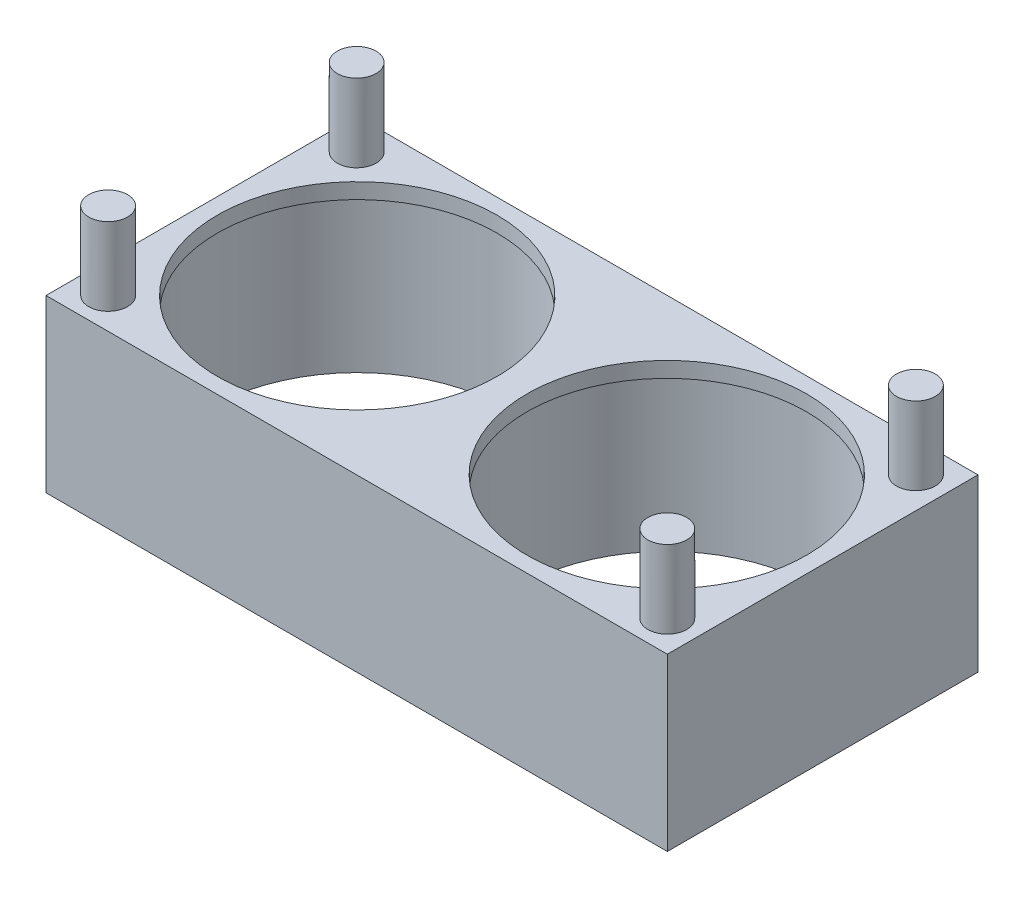
SolidWorks part; units mm, degrees
material "PBT General Purpose"
ref_plane "Front Plane" through (0, 0, 0) normal (0, 0, 1) x (1, 0, 0)
ref_plane "Top Plane" through (0, 0, 0) normal (0, 1, 0) x (1, 0, 0)
ref_plane "Right Plane" through (0, 0, 0) normal (1, 0, 0) x (0, 0, -1)
sketch "Sketch1" plane through (0, 0, 0) normal (0, 1, 0) x (1, 0, 0)
  line L1 (0, 0) -> (80, 0)
  line L2 (0, 0) -> (0, 40)
  line L3 (0, 40) -> (80, 40)
  line L4 (80, 0) -> (80, 40)
  dimension "D1" = 80
  dimension "D2" = 40
extrude "Boss-Extrude1" add sketch "Sketch1" along normal blind 22
sketch "Sketch2" plane through (0, 0, 0) normal (0, -1, 0) x (1, 0, 0)
  line L0 (0, -20) -> (20.07, -20) construction
  line L1 (0, -40) -> (0, 0) construction
  line L2 (80, -20) -> (59.93, -20) construction
  line L3 (80, 0) -> (80, -40) construction
  circle A0 centre (20.07, -20) radius 19
  circle A1 centre (59.93, -20) radius 19
  dimension "D1" = 38
  dimension "D2" = 39.86
extrude "Cut-Extrude1" cut sketch "Sketch2" against normal blind 20
sketch "Sketch3" plane through (0, 20, 0) normal (0, -1, 0) x (1, 0, 0)
  circle A0 centre (20.07, -20) radius 18
  circle A1 centre (59.93, -20) radius 18
  circle A2 centre (59.93, -20) radius 19 construction
  circle A3 centre (20.07, -20) radius 19 construction
  dimension "D1" = 36
extrude "Cut-Extrude2" cut sketch "Sketch3" against normal through all
sketch "Sketch4" plane through (0, 22, 0) normal (0, 1, 0) x (1, 0, 0)
  line L0 (4, 4) -> (76, 4) construction
  line L1 (76, 4) -> (76, 36) construction
  line L2 (76, 36) -> (4, 36) construction
  line L3 (4, 36) -> (4, 4) construction
  line L4 (0, 20) -> (4, 20) construction
  line L5 (0, 40) -> (0, 0) construction
  line L6 (40, 4) -> (40, 0) construction
  line L7 (0, 0) -> (80, 0) construction
  line L8 (80, 40) -> (0, 40) construction
  circle A0 centre (4, 36) radius 2.5
  circle A1 centre (76, 36) radius 2.5
  circle A2 centre (76, 4) radius 2.5
  circle A3 centre (4, 4) radius 2.5
  dimension "D1" = 5
  dimension "D2" = 4
  dimension "D3" = 4
extrude "Boss-Extrude2" add sketch "Sketch4" along normal blind 10
